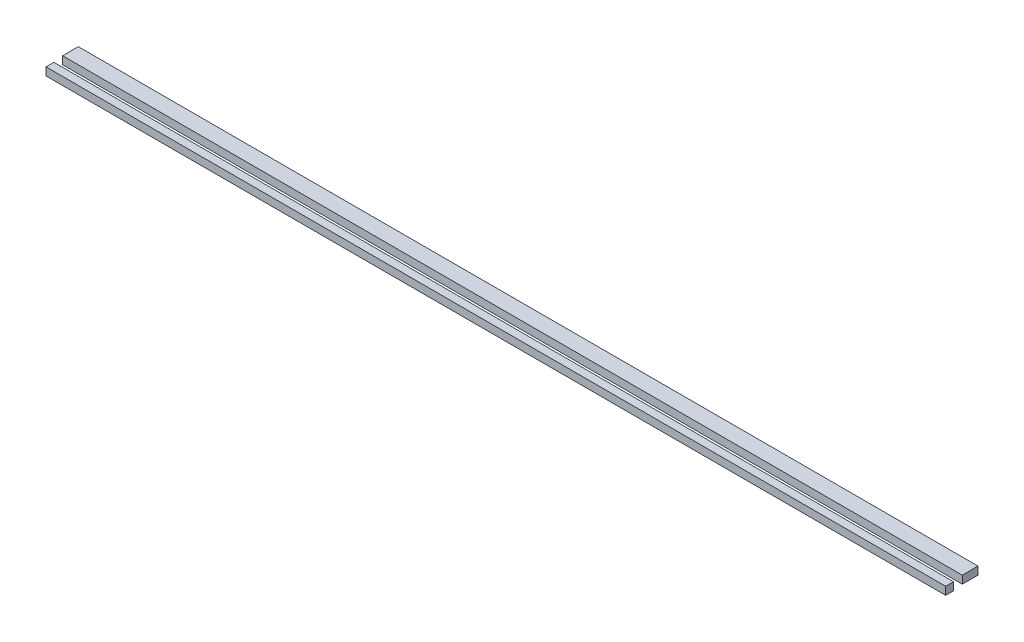
SolidWorks part; units mm, degrees
ref_plane "Front Plane" through (0, 0, 0) normal (0, 0, 1) x (1, 0, 0)
ref_plane "Top Plane" through (0, 0, 0) normal (0, 1, 0) x (1, 0, 0)
ref_plane "Right Plane" through (0, 0, 0) normal (1, 0, 0) x (0, 0, -1)
sketch "Sketch1" plane through (0, 0, 0) normal (0, 1, 0) x (1, 0, 0)
  line L1 (-170.544, 99.8027) -> (172.456, 99.8027)
  line L2 (-170.544, 99.8027) -> (-170.544, 93.8027)
  line L3 (-170.544, 93.8027) -> (172.456, 93.8027)
  line L4 (172.456, 99.8027) -> (172.456, 93.8027)
  dimension "D1" = 343
  dimension "D2" = 6
extrude "Boss-Extrude1" add sketch "Sketch1" along normal blind 3
sketch "Sketch2" plane through (0, 0, 0) normal (0, 1, 0) x (1, 0, 0)
  line L1 (-132.4256, 39.0183) -> (210.5744, 39.0183)
  line L2 (-132.4256, 39.0183) -> (-132.4256, 36.0183)
  line L3 (-132.4256, 36.0183) -> (210.5744, 36.0183)
  line L4 (210.5744, 39.0183) -> (210.5744, 36.0183)
  dimension "D1" = 343
  dimension "D2" = 3
extrude "Boss-Extrude2" add sketch "Sketch2" along normal blind 3 separate body
move or copy body "Body-Move/Copy1" bodies to move or copy 102 copy no translate (-37.6174, 0, -50.9532)
